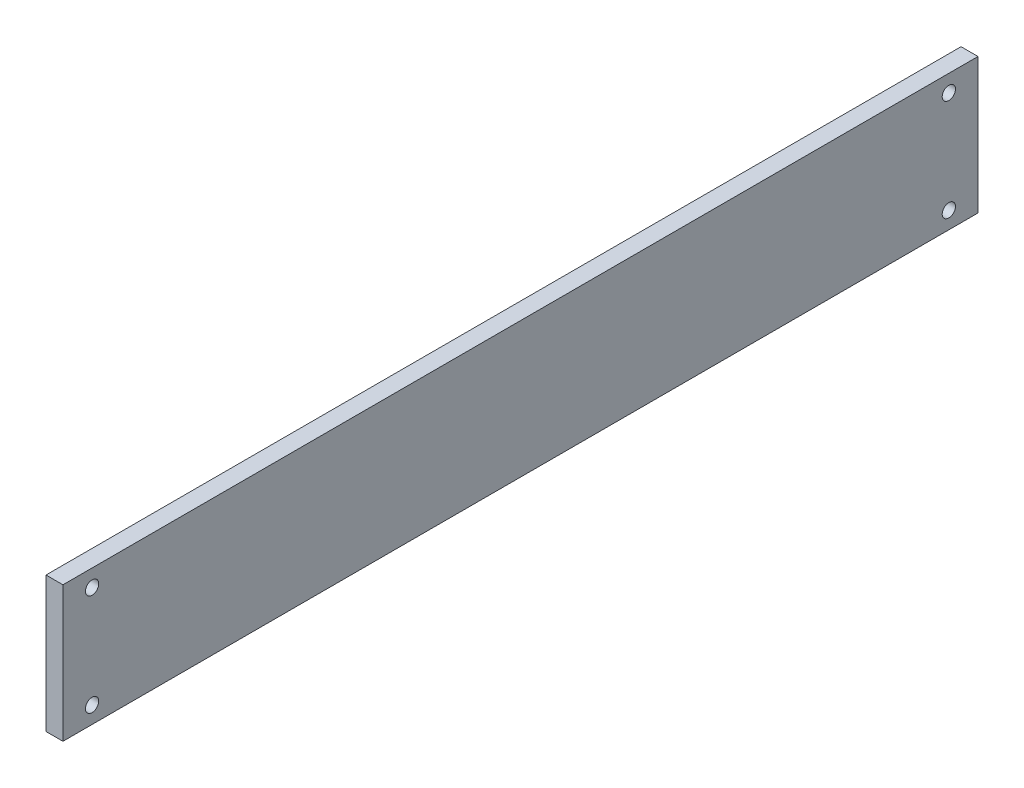
SolidWorks part; units mm, degrees
material "6061-T6 (SS)"
ref_plane "Front Plane" through (0, 0, 0) normal (0, 0, 1) x (1, 0, 0)
ref_plane "Top Plane" through (0, 0, 0) normal (0, 1, 0) x (1, 0, 0)
ref_plane "Right Plane" through (0, 0, 0) normal (1, 0, 0) x (0, 0, -1)
sketch "Sketch1" plane through (0, 0, 0) normal (1, 0, 0) x (0, 0, -1)
  line L1 (-171.45, 25.4) -> (171.45, 25.4)
  line L2 (-171.45, 25.4) -> (-171.45, -25.4)
  line L3 (-171.45, -25.4) -> (171.45, -25.4)
  line L4 (171.45, 25.4) -> (171.45, -25.4)
  line L5 (-171.45, 25.4) -> (171.45, -25.4) construction
  line L6 (-171.45, -25.4) -> (171.45, 25.4) construction
  line L7 (160.528, 19.05) -> (-160.528, 19.05) construction
  line L8 (160.528, 19.05) -> (160.528, -19.05) construction
  line L9 (160.528, -19.05) -> (-160.528, -19.05) construction
  line L10 (-160.528, 19.05) -> (-160.528, -19.05) construction
  line L11 (160.528, 19.05) -> (-160.528, -19.05) construction
  line L12 (160.528, -19.05) -> (-160.528, 19.05) construction
  circle A0 centre (-160.528, 19.05) radius 2.4892
  circle A1 centre (-160.528, -19.05) radius 2.4892
  circle A2 centre (160.528, -19.05) radius 2.4892
  circle A3 centre (160.528, 19.05) radius 2.4892
  point P0 (0, 0)
  point P6 (0, 0)
  dimension "D3" = 4.9784
  dimension "D1" = 50.8
  dimension "D2" = 342.9
  dimension "D4" = 38.1
  dimension "D5" = 10.922
extrude "Boss-Extrude1" add sketch "Sketch1" along normal blind 6.35
